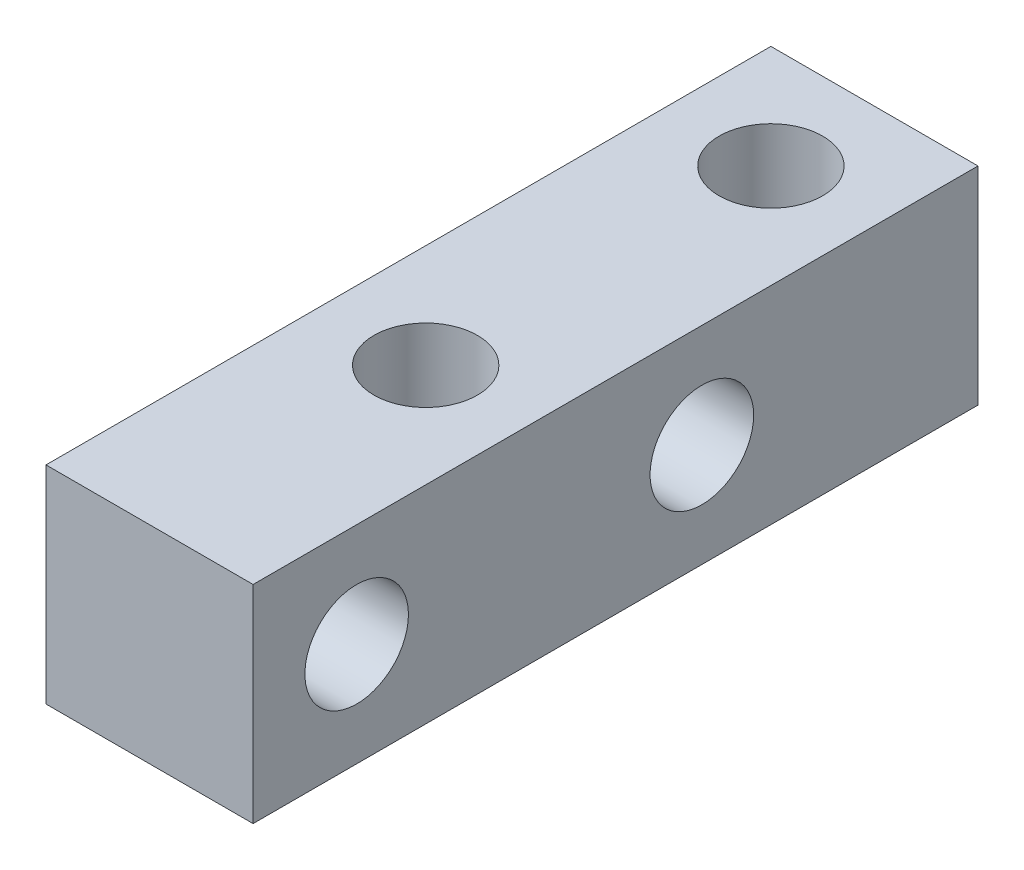
SolidWorks part; units mm, degrees
ref_plane "前视基准面" through (0, 0, 0) normal (0, 0, 1) x (1, 0, 0)
ref_plane "上视基准面" through (0, 0, 0) normal (0, 1, 0) x (1, 0, 0)
ref_plane "右视基准面" through (0, 0, 0) normal (1, 0, 0) x (0, 0, -1)
sketch "草图1" plane through (0, 0, 0) normal (0, 0, 1) x (1, 0, 0)
  line L1 (-3, -3) -> (3, -3)
  line L2 (-3, -3) -> (-3, 3)
  line L3 (-3, 3) -> (3, 3)
  line L4 (3, -3) -> (3, 3)
  line L5 (-3, -3) -> (3, 3) construction
  line L6 (-3, 3) -> (3, -3) construction
  point P0 (0, 0)
  dimension "D1" = 6
  dimension "D2" = 6
extrude "凸台-拉伸1" add sketch "草图1" along normal blind 21
sketch "草图2" plane through (0, 3, 0) normal (0, 1, 0) x (1, 0, 0)
  line L0 (0, 0) -> (0, -21) construction
  line L1 (3, 0) -> (-3, 0) construction
  line L2 (3, -21) -> (-3, -21) construction
  circle A0 centre (0, -3) radius 1.5
  circle A1 centre (0, -13) radius 1.5
  dimension "D3" = 3
  dimension "D1" = 3
  dimension "D2" = 10
extrude "切除-拉伸1" cut sketch "草图2" against normal through all
sketch "草图3" plane through (3, 0, 0) normal (1, 0, 0) x (0, 0, -1)
  line L0 (-21, 0) -> (0, 0) construction
  line L1 (-21, -3) -> (-21, 3) construction
  circle A0 centre (-18, 0) radius 1.5
  circle A1 centre (-8, 0) radius 1.5
  dimension "D3" = 3
  dimension "D1" = 3
  dimension "D2" = 10
extrude "切除-拉伸2" cut sketch "草图3" against normal through all
